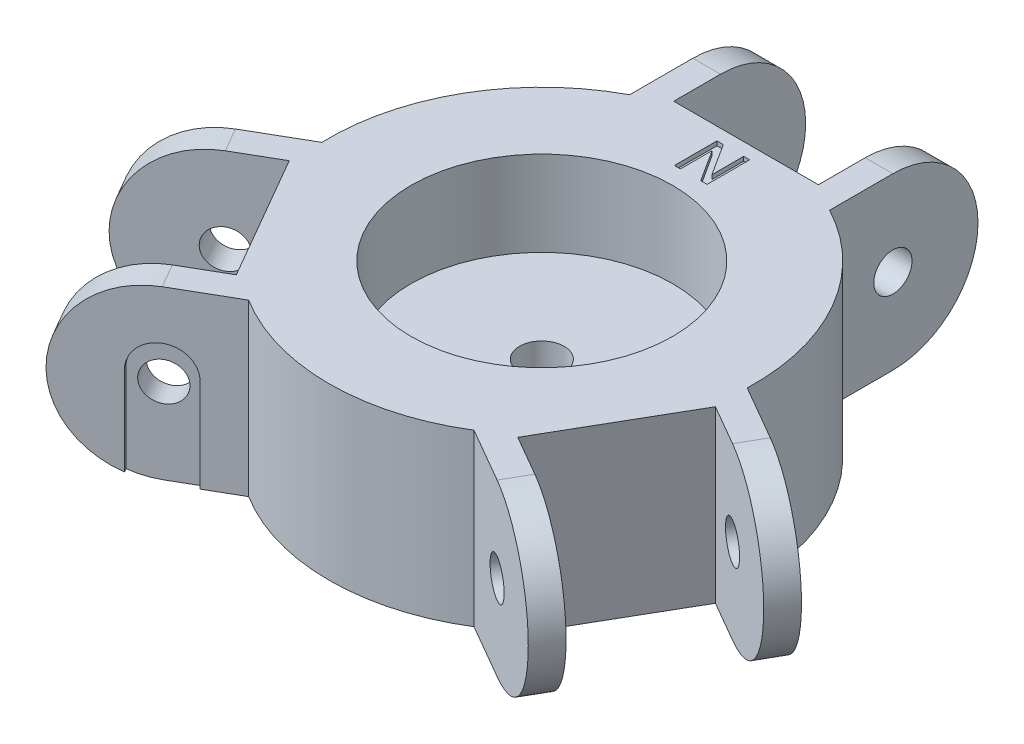
SolidWorks part; units mm, degrees
material "STAINLESS STEEL, 304"
ref_plane "Front Plane" through (0, 0, 0) normal (0, 0, 1) x (1, 0, 0)
ref_plane "Top Plane" through (0, 0, 0) normal (0, 1, 0) x (1, 0, 0)
ref_plane "Right Plane" through (0, 0, 0) normal (1, 0, 0) x (0, 0, -1)
sketch "Sketch1" plane through (0, 0, 0) normal (0, 1, 0) x (1, 0, 0)
  circle A0 centre (0, 0) radius 50
  dimension "D1" = 100
extrude "Boss-Extrude1" add sketch "Sketch1" along normal blind 40
sketch "Sketch2" plane through (0, 40, 0) normal (0, 1, 0) x (1, 0, 0)
  circle A0 centre (0, 0) radius 30.75
  dimension "D1" = 61.5
extrude "Cut-Extrude1" cut sketch "Sketch2" against normal blind 20
hole_wizard "Ø10.5 (10.5) Diameter Hole1" positions "Sketch3" profile "Sketch4" hole size "Ø10.5" standard "ISO" end condition up to next
sketch "Sketch3" plane through (0, 20, 0) normal (0, 1, 0) x (1, 0, 0)
  point P0 (0, 0)
sketch "Sketch4" plane through (0, 20, 0) normal (1, 0, 0) x (0, 0, 1)
  line L0 (0, 0) -> (0, 20)
  line L1 (0, 20) -> (5.25, 20)
  line L2 (5.25, 20) -> (5.25, 0)
  line L5 (5.25, 0) -> (0, 0)
  line L11 (0, -6.35) -> (0, 107.95) construction
  dimension "Thru Hole Dia." = 10.5
  dimension "Thru Hole Depth" = 20
sketch "Sketch5" plane through (0, 40, 0) normal (0, 1, 0) x (1, 0, 0)
  line L3 (-14, 48) -> (14, 48)
  circle A0 centre (0, 0) radius 50 construction
  arc A1 (14, 48) -> (-14, 48) centre (0, 0) ccw
  dimension "D1" = 98
extrude "Cut-Extrude2" cut sketch "Sketch5" against normal through all contours L3 A1
sketch "Sketch6" plane through (0, 0, -48) normal (0, 0, -1) x (-1, 0, 0)
  line L0 (14, 40) -> (-14, 40) construction
  line L1 (-23.5, 40) -> (23.5, 40)
  line L2 (-23.5, 40) -> (-23.5, 0)
  line L3 (-23.5, 0) -> (23.5, 0)
  line L4 (23.5, 40) -> (23.5, 0)
  dimension "D1" = 47
extrude "Boss-Extrude2" add sketch "Sketch6" against normal up to next
sketch "Sketch7" plane through (-23.5, 0, 0) normal (-1, 0, 0) x (0, 0, 1)
  line L0 (-59, 40) -> (-48, 40)
  line L1 (-48, 40) -> (-48, 0)
  line L2 (-48, 0) -> (-59, 0)
  line L3 (-44.1333, 0) -> (-44.1333, 40) construction
  arc A0 (-59, 40) -> (-59, 0) centre (-59, 20) ccw
  dimension "D1" = 11
  dimension "D2" = 59
  dimension "D3" = 14.8667
extrude "Boss-Extrude3" add sketch "Sketch7" against normal blind 6.5
hole_wizard "Ø9.0 (9) Diameter Hole1" positions "Sketch8" profile "Sketch9" hole size "Ø9.0" standard "ISO" end condition up to next
sketch "Sketch8" plane through (-23.5, 0, 0) normal (-1, 0, 0) x (0, 0, 1)
  point P0 (-59, 20)
sketch "Sketch9" plane through (-23.5, 20, -59) normal (0, 1, 0) x (0, 0, 1)
  line L0 (0, 0) -> (0, 6.5)
  line L1 (0, 6.5) -> (4.5, 6.5)
  line L2 (4.5, 6.5) -> (4.5, 0)
  line L5 (4.5, 0) -> (0, 0)
  line L11 (0, -6.35) -> (0, 107.95) construction
  dimension "Thru Hole Dia." = 9
  dimension "Thru Hole Depth" = 6.5
mirror "Mirror1" about plane through (0, 0, 0) normal (1, 0, 0) of "Boss-Extrude3", "Ø9.0 (9) Diameter Hole1"
sketch "Sketch10" plane through (-23.5, 0, 0) normal (-1, 0, 0) x (0, 0, 1)
  line L0 (-65.5, 22) -> (-65.5, 0)
  line L1 (-65.5, 0) -> (-52.5, 0)
  line L2 (-52.5, 0) -> (-52.5, 22)
  line L3 (-59, 0) -> (-59, 20) construction
  line L4 (-44.1333, 0) -> (-59, 0) construction
  arc A0 (-65.5, 22) -> (-52.5, 22) centre (-59, 22) cw
  dimension "D1" = 13
  dimension "D2" = 22
extrude "Cut-Extrude3" cut sketch "Sketch10" against normal blind 1
pattern_circular "CirPattern1" count 3 over 360 about axis through (0, 0, 0) along (0, 1, 0) of "Cut-Extrude2", "Boss-Extrude2", "Boss-Extrude3", "Ø9.0 (9) Diameter Hole1", "Mirror1", "Cut-Extrude3"
sketch "Sketch11" plane through (0, 40, 0) normal (0, 1, 0) x (1, 0, 0)
  line L0 (-23.5, 35) -> (23.5, 35) construction
  line L1 (-23.5, 44.1333) -> (-23.5, 59) construction
  line L2 (23.5, 44.1333) -> (23.5, 59) construction
  circle A0 centre (0, 0) radius 5.25 construction
  text T0 "N" font "Arial" height 10
  dimension "D1" = 35
extrude "Cut-Extrude4" cut sketch "Sketch11" against normal blind 1
